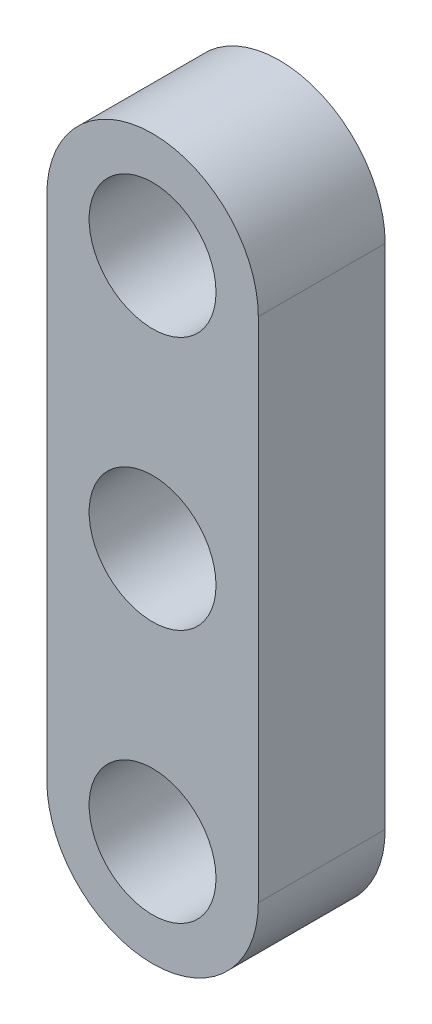
SolidWorks part; units mm, degrees
ref_plane "Plan de face" through (0, 0, 0) normal (0, 0, 1) x (1, 0, 0)
ref_plane "Plan de dessus" through (0, 0, 0) normal (0, 1, 0) x (1, 0, 0)
ref_plane "Plan de droite" through (0, 0, 0) normal (1, 0, 0) x (0, 0, -1)
sketch "Esquisse2" plane through (0, 0, -3.518) normal (0, 0, 1) x (1, 0, 0)
  line L0 (25, 4) -> (25, 16)
  line L1 (30, 4) -> (30, 16)
  arc A0 (30, 16) -> (25, 16) centre (27.5, 16) ccw
  arc A1 (30, 4) -> (25, 4) centre (27.5, 4) cw
  circle A3 centre (27.5, 16) radius 1.5
  circle A4 centre (27.5, 4) radius 1.5
  circle A5 centre (27.5, 10) radius 1.5
  point P4 (27.5, 4)
  dimension "D2" = 3
  dimension "D1" = 12
extrude "Boss.-Extru.1" add sketch "Esquisse2" along normal blind 3
